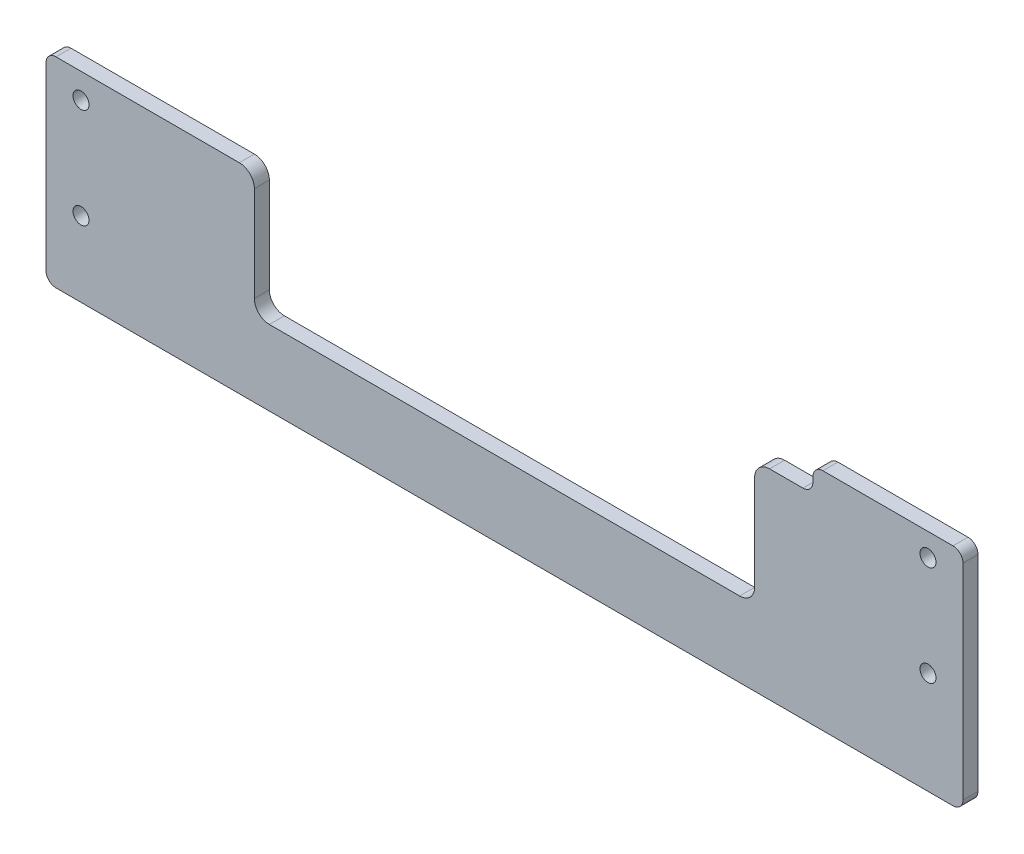
SolidWorks part; units mm, degrees
material "A-玻璃纤维"
ref_plane "前视基准面" through (0, 0, 0) normal (0, 0, 1) x (1, 0, 0)
ref_plane "上视基准面" through (0, 0, 0) normal (0, 1, 0) x (1, 0, 0)
ref_plane "右视基准面" through (0, 0, 0) normal (1, 0, 0) x (0, 0, -1)
other "Configuration Table"
sketch "草图1" plane through (0, 0, 0) normal (0, 0, 1) x (1, 0, 0)
  line L1 (0, 0) -> (183.3, 0)
  line L2 (0, 0) -> (0, 40)
  line L3 (0, 40) -> (153.3, 40)
  line L4 (183.3, 0) -> (183.3, 40)
  line L6 (183.3, 40) -> (183.3, 45)
  line L7 (183.3, 45) -> (153.3, 45)
  line L8 (153.3, 40) -> (153.3, 45)
  dimension "D1" = 183.3
  dimension "D2" = 40
  dimension "D3" = 5
  dimension "D4" = 30
extrude "凸台-拉伸1" add sketch "草图1" along normal blind 3
fillet "圆角1" radius 2 6 edges at (183.3, 0, 1.5) (0, 0, 1.5) (0, 40, 1.5) (183.3, 45, 1.5) (153.3, 45, 1.5) (153.3, 40, 1.5)
sketch "草图2" plane through (0, 0, 0) normal (0, 0, -1) x (-1, 0, 0)
  line L1 (-151.3, 40) -> (-2, 40) construction
  line L2 (-2, 0) -> (-181.3, 0) construction
  line L3 (-176.3, 40) -> (-176.3, 0) construction
  line L4 (-183.3, 2) -> (-183.3, 43) construction
  line L5 (-7, 40) -> (-7, 0) construction
  line L6 (0, 38) -> (0, 2) construction
  circle A0 centre (-176.3, 40.44) radius 1.6
  circle A1 centre (-176.3, 20.44) radius 1.6
  circle A4 centre (-7, 35) radius 1.6
  circle A5 centre (-7, 15) radius 1.6
  dimension "D2" = 3.2
  dimension "D3" = 20
  dimension "D4" = 20.44
  dimension "D6" = 3.2
  dimension "D7" = 3.2
  dimension "D8" = 20
  dimension "D9" = 15
  dimension "D1" = 7
  dimension "D5" = 7
extrude "切除-拉伸1" cut sketch "草图2" against normal blind 14
sketch "草图3" plane through (0, 0, 0) normal (0, 0, -1) x (-1, 0, 0)
  line L0 (-151.3, 40) -> (-2, 40) construction
  line L1 (-141.65, 40) -> (-41.65, 40)
  line L2 (-141.65, 40) -> (-141.65, 15)
  line L3 (-141.65, 15) -> (-41.65, 15)
  line L4 (-41.65, 40) -> (-41.65, 15)
  line L6 (-91.65, 40) -> (-91.65, 0) construction
  line L7 (-2, 0) -> (-181.3, 0) construction
  point P10 (-91.65, 0)
  dimension "D1" = 25
  dimension "D2" = 50
extrude "切除-拉伸2" cut sketch "草图3" against normal blind 14
fillet "圆角2" radius 3 4 edges at (41.65, 40, 1.5) (41.65, 15, 1.5) (141.65, 15, 1.5) (141.65, 40, 1.5)
